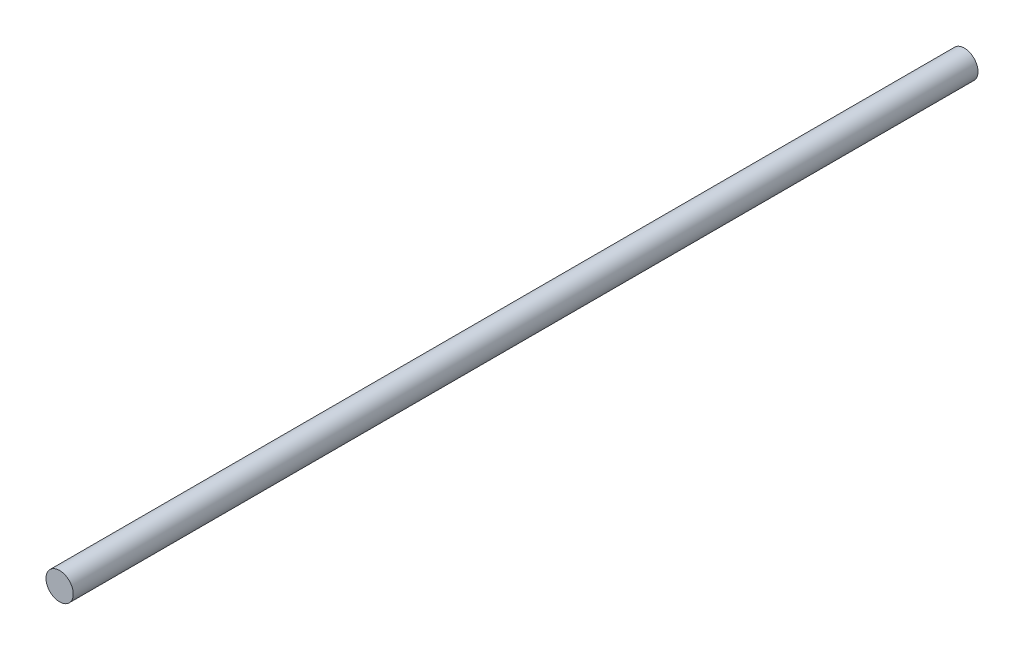
SolidWorks part; units mm, degrees
ref_plane "Front Plane" through (0, 0, 0) normal (0, 0, 1) x (1, 0, 0)
ref_plane "Top Plane" through (0, 0, 0) normal (0, 1, 0) x (1, 0, 0)
ref_plane "Right Plane" through (0, 0, 0) normal (1, 0, 0) x (0, 0, -1)
sketch "Sketch1" plane through (0, 0, 0) normal (0, 0, 1) x (1, 0, 0)
  circle A0 centre (0, 0) radius 3.175
extrude "Extrude1" add sketch "Sketch1" along normal blind 210.82
